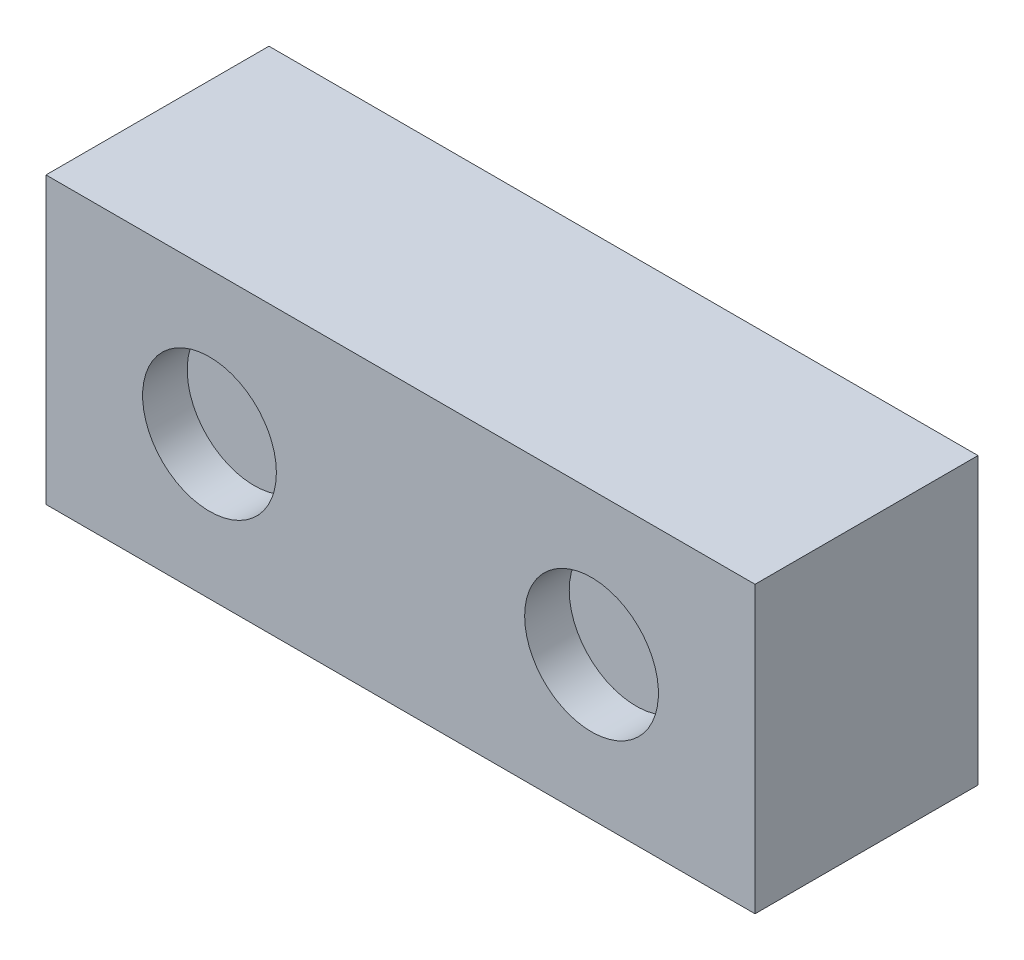
SolidWorks part; units mm, degrees
ref_plane "Alzado" through (0, 0, 0) normal (0, 0, 1) x (1, 0, 0)
ref_plane "Planta" through (0, 0, 0) normal (0, 1, 0) x (1, 0, 0)
ref_plane "Vista lateral" through (0, 0, 0) normal (1, 0, 0) x (0, 0, -1)
sketch "Croquis1" plane through (0, 0, 0) normal (0, 0, 1) x (1, 0, 0)
  line L1 (-15.9, 6.4) -> (15.9, 6.4)
  line L2 (-15.9, 6.4) -> (-15.9, -6.4)
  line L3 (-15.9, -6.4) -> (15.9, -6.4)
  line L4 (15.9, 6.4) -> (15.9, -6.4)
  line L5 (-15.9, 6.4) -> (15.9, -6.4) construction
  line L6 (-15.9, -6.4) -> (15.9, 6.4) construction
  point P0 (0, 0)
  dimension "D1" = 12.8
  dimension "31.8" = 31.8
extrude "Saliente-Extruir1" add sketch "Croquis1" along normal blind 10
sketch "Croquis2" plane through (0, 0, 10) normal (0, 0, 1) x (1, 0, 0)
  line L0 (0, 6.4) -> (0, -6.4) construction
  line L1 (15.9, 6.4) -> (-15.9, 6.4) construction
  line L2 (-15.9, -6.4) -> (15.9, -6.4) construction
  circle A0 centre (-8.5671, 0) radius 3
extrude "Cortar-Extruir1" cut sketch "Croquis2" against normal blind 2
mirror "Simetría1" about plane through (0, 0, 0) normal (1, 0, 0) of "Cortar-Extruir1"
